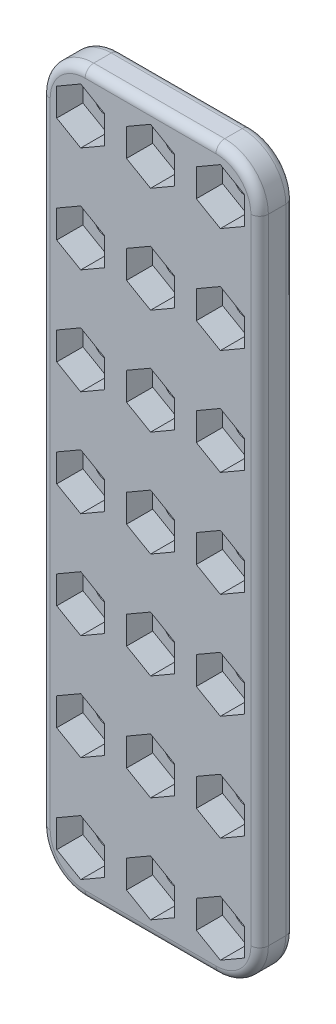
SolidWorks part; units mm, degrees
ref_plane "Front Plane" through (0, 0, 0) normal (0, 0, 1) x (1, 0, 0)
ref_plane "Top Plane" through (0, 0, 0) normal (0, 1, 0) x (1, 0, 0)
ref_plane "Right Plane" through (0, 0, 0) normal (1, 0, 0) x (0, 0, -1)
sketch "草图1" plane through (0, 0, 0) normal (0, 0, 1) x (1, 0, 0)
  line L1 (-12.5, 5) -> (12.5, 5)
  line L2 (-12.5, 5) -> (-12.5, -5)
  line L3 (-12.5, -5) -> (12.5, -5)
  line L4 (12.5, 5) -> (12.5, -5)
  line L5 (-12.5, 5) -> (12.5, -5) construction
  line L6 (-12.5, -5) -> (12.5, 5) construction
  point P0 (0, 0)
  dimension "D1" = 25
  dimension "D2" = 10
extrude "凸台-拉伸1" add sketch "草图1" along normal blind 4
sketch "草图2" plane through (0, 0, 4) normal (0, 0, 1) x (1, 0, 0)
  line L0 (0, -1000) -> (0, 49000) construction
  circle A0 centre (0, 0) radius 1.5
  circle A1 centre (-8, 0) radius 1.5
  circle A2 centre (8, 0) radius 1.5
  dimension "D1" = 3
  dimension "D2" = 3
  dimension "D3" = 16
sketch "草图3" plane through (0, 0, 4) normal (0, 0, 1) x (1, 0, 0)
  line L19 (-8, 3.1754) -> (-10.75, 1.5877)
  line L20 (-10.75, 1.5877) -> (-10.75, -1.5877)
  line L21 (-10.75, -1.5877) -> (-8, -3.1754)
  line L22 (-8, -3.1754) -> (-5.25, -1.5877)
  line L23 (-5.25, -1.5877) -> (-5.25, 1.5877)
  line L24 (-5.25, 1.5877) -> (-8, 3.1754)
  line L25 (0, 3.1754) -> (-2.75, 1.5877)
  line L26 (-2.75, 1.5877) -> (-2.75, -1.5877)
  line L27 (-2.75, -1.5877) -> (0, -3.1754)
  line L28 (0, -3.1754) -> (2.75, -1.5877)
  line L29 (2.75, -1.5877) -> (2.75, 1.5877)
  line L30 (2.75, 1.5877) -> (0, 3.1754)
  line L31 (8, 3.1754) -> (5.25, 1.5877)
  line L32 (5.25, 1.5877) -> (5.25, -1.5877)
  line L33 (5.25, -1.5877) -> (8, -3.1754)
  line L34 (8, -3.1754) -> (10.75, -1.5877)
  line L35 (10.75, -1.5877) -> (10.75, 1.5877)
  line L36 (10.75, 1.5877) -> (8, 3.1754)
  circle A1 centre (-8, 0) radius 2.75 construction
  circle A2 centre (0, 0) radius 2.75 construction
  circle A3 centre (8, 0) radius 2.75 construction
  dimension "D1" = 5.5
extrude "切除-拉伸1" cut sketch "草图2" against normal through all
extrude "切除-拉伸2" cut sketch "草图3" against normal blind 3
sketch "草图4" plane through (0, 0, 4) normal (0, 0, 1) x (1, 0, 0)
  line L0 (0, -1000) -> (0, 49000) construction
  line L1 (-1000, 0) -> (49000, 0) construction
  line L2 (-1000, -12.1) -> (49000, -12.1) construction
  line L4 (-12.5, -5) -> (12.5, -5)
  line L5 (-12.5, -5) -> (-12.5, -17.1)
  line L6 (-12.5, -17.1) -> (12.5, -17.1)
  line L7 (12.5, -5) -> (12.5, -17.1)
  dimension "D1" = 12.1
  dimension "D2" = 12.1
extrude "凸台-拉伸2" add sketch "草图4" against normal up to surface (4 mm away) contours L5 L6 L7 L4 up to face at (6.5, 0, 0)
sketch "草图5" plane through (0, 0, 4) normal (0, 0, 1) x (1, 0, 0)
  line L0 (0, -201000) -> (0, 249000) construction
  line L1 (-201000, -12.1) -> (249000, -12.1) construction
  line L2 (0, -1000) -> (0, 49000) construction
  circle A0 centre (0, -12.1) radius 1.5
  circle A1 centre (-8, -12.1) radius 1.5
  circle A2 centre (8, -12.1) radius 1.5
  dimension "D1" = 3
  dimension "D2" = 3
  dimension "D3" = 16
sketch "草图6" plane through (0, 0, 4) normal (0, 0, 1) x (1, 0, 0)
  line L1 (-8, -8.9246) -> (-10.75, -10.5123)
  line L2 (-10.75, -10.5123) -> (-10.75, -13.6877)
  line L3 (-10.75, -13.6877) -> (-8, -15.2754)
  line L4 (-8, -15.2754) -> (-5.25, -13.6877)
  line L5 (-5.25, -13.6877) -> (-5.25, -10.5123)
  line L6 (-5.25, -10.5123) -> (-8, -8.9246)
  line L7 (0, -8.9246) -> (-2.75, -10.5123)
  line L8 (-2.75, -10.5123) -> (-2.75, -13.6877)
  line L9 (-2.75, -13.6877) -> (0, -15.2754)
  line L10 (0, -15.2754) -> (2.75, -13.6877)
  line L11 (2.75, -13.6877) -> (2.75, -10.5123)
  line L12 (2.75, -10.5123) -> (0, -8.9246)
  line L13 (8, -8.9246) -> (5.25, -10.5123)
  line L14 (5.25, -10.5123) -> (5.25, -13.6877)
  line L15 (5.25, -13.6877) -> (8, -15.2754)
  line L16 (8, -15.2754) -> (10.75, -13.6877)
  line L17 (10.75, -13.6877) -> (10.75, -10.5123)
  line L18 (10.75, -10.5123) -> (8, -8.9246)
  circle A0 centre (-8, -12.1) radius 2.75 construction
  circle A1 centre (0, -12.1) radius 2.75 construction
  circle A2 centre (8, -12.1) radius 2.75 construction
  dimension "D1" = 5.5
extrude "切除-拉伸3" cut sketch "草图5" against normal through all
extrude "切除-拉伸4" cut sketch "草图6" against normal blind 3
pattern_linear "阵列(线性)1" count 6 spacing 12.1 along (0, -1, 0) of "切除-拉伸4", "切除-拉伸3", "凸台-拉伸2"
fillet "圆角1" radius 5 4 edges at (12.5, 5, 2) (-12.5, 5, 2) (12.5, -77.6, 2) (-12.5, -77.6, 2)
fillet "圆角2" radius 1 16 edges at (11.0355, 3.5355, 4) (11.0355, 3.5355, 0) (12.5, -36.3, 4) (12.5, -36.3, 0) (-12.5, -36.3, 4) (-12.5, -36.3, 0) (-11.0355, 3.5355, 4) (-11.0355, 3.5355, 0) (0, 5, 4) (0, 5, 0) (11.0355, -76.1355, 0) (11.0355, -76.1355, 4) (0, -77.6, 4) (-11.0355, -76.1355, 0) (-11.0355, -76.1355, 4) (0, -77.6, 0)
